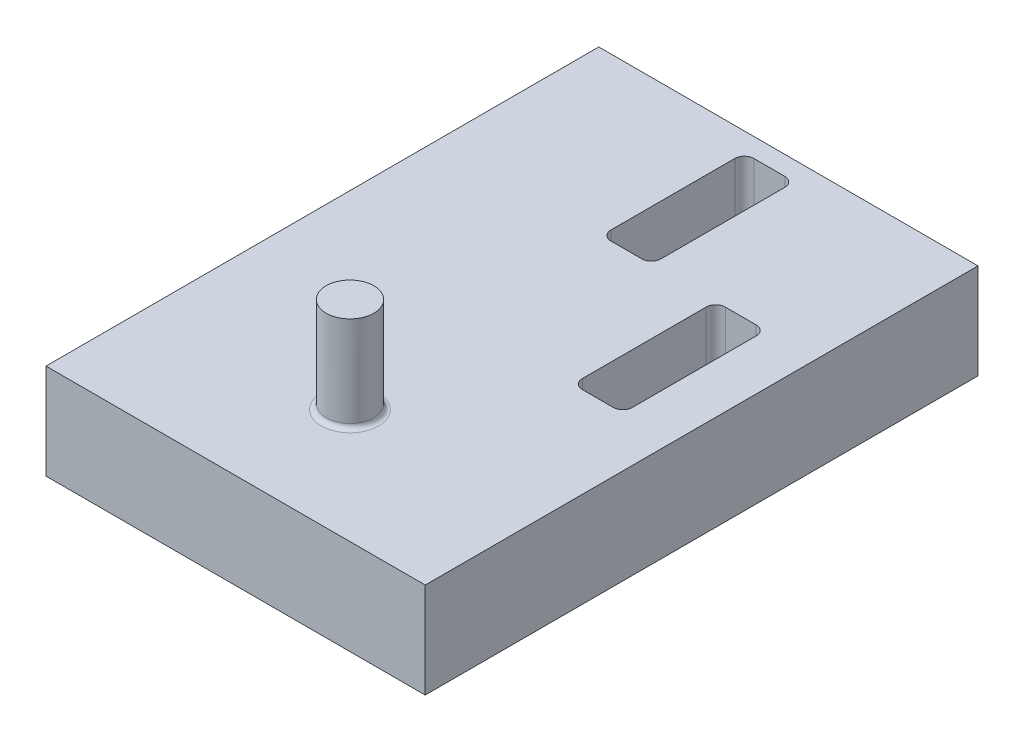
SolidWorks part; units mm, degrees
ref_plane "Front Plane" through (0, 0, 0) normal (0, 0, 1) x (1, 0, 0)
ref_plane "Top Plane" through (0, 0, 0) normal (0, 1, 0) x (1, 0, 0)
ref_plane "Right Plane" through (0, 0, 0) normal (1, 0, 0) x (0, 0, -1)
sketch "10" plane through (0, 0, 0) normal (0, 1, 0) x (1, 0, 0)
  line L0 (-15, 31.5) -> (15, 31.5) construction
  line L1 (-14.8938, 29.7182) -> (14.8938, 33.2818)
  line L2 (-14.8938, 29.7182) -> (-12, 15)
  line L3 (14.8938, 33.2818) -> (12, 48)
  line L4 (-12, 15) -> (0, 15)
  line L5 (12, 48) -> (0, 48)
  line L6 (0, 48) -> (0, 63)
  line L7 (0, 15) -> (0, 0)
  point P4 (0, 31.5)
  point P5 (0, 31.5)
  dimension "D1" = 15
  dimension "D2" = 12
  dimension "D3" = 15
  dimension "D4" = 30
  dimension "D5" = 30
  dimension "D6" = 15
  dimension "D7" = 0
  dimension "D8" = 0
  dimension "D9" = 31.5
sketch "01" plane through (0, 0, 0) normal (0, 1, 0) x (1, 0, 0)
  line L0 (-15, 31.5) -> (15, 31.5) construction
  line L1 (-9.3393, 19.7621) -> (9.3393, 43.2379)
  line L2 (-9.3393, 19.7621) -> (-12, 5)
  line L3 (9.3393, 43.2379) -> (12, 58)
  line L4 (-12, 5) -> (0, 5)
  line L5 (12, 58) -> (0, 58)
  line L6 (0, 58) -> (0, 73)
  line L7 (0, 5) -> (0, -10)
  point P4 (0, 31.5)
  point P5 (0, 31.5)
  dimension "D1" = 30
  dimension "D2" = 15
  dimension "D3" = 12
  dimension "D4" = 15
  dimension "D5" = 30
  dimension "D6" = 0
  dimension "D7" = 41.5
  dimension "D8" = 0
  dimension "D9" = 15
sketch "Sketch2" plane through (0, 0, 0) normal (0, 1, 0) x (1, 0, 0)
  line L1 (-19.8938, 77.5) -> (0, 77.5)
  line L2 (-19.8938, 77.5) -> (-19.8938, -14.5)
  line L3 (-19.8938, -14.5) -> (0, -14.5)
  line L9 (-15, 31.5) -> (15, 31.5) construction
  line L24 (0, 77.5) -> (0, 75.5)
  line L25 (-2.625, 73) -> (-2.625, 63)
  line L26 (0, 75.5) -> (-2.625, 75.5)
  line L27 (-2.625, 75.5) -> (-2.625, 73)
  line L28 (0, 60.5) -> (-2.625, 60.5)
  line L29 (-2.625, 60.5) -> (-2.625, 63)
  line L32 (0, 60.375) -> (0, 2.5)
  line L34 (0, 60.5) -> (0, 60.375)
  line L35 (-2.625, 0) -> (-2.625, -10)
  line L36 (0, 2.5) -> (-2.625, 2.5)
  line L37 (-2.625, 2.5) -> (-2.625, 0)
  line L38 (0, -12.5) -> (-2.625, -12.5)
  line L39 (-2.625, -12.5) -> (-2.625, -10)
  line L41 (0, -12.5) -> (0, -14.5)
  circle A7 centre (-14.8938, 29.7182) radius 5 construction
  circle A19 centre (0, 73) radius 2.625 construction
  circle A21 centre (0, 63) radius 2.625 construction
  circle A22 centre (0, 73) radius 2.5 construction
  circle A23 centre (0, 63) radius 2.5 construction
  circle A24 centre (0, -10) radius 2.625 construction
  circle A25 centre (0, 0) radius 2.625 construction
  circle A26 centre (0, 0) radius 2.5 construction
  circle A27 centre (0, -10) radius 2.5 construction
  dimension "D2" = 5.25
  dimension "D3" = 5.25
  dimension "D4" = 5
  dimension "D5" = 5
  dimension "D8" = 10
  dimension "D7" = 10
  dimension "D9" = 5.25
  dimension "D12" = 5.25
  dimension "D14" = 5
  dimension "D15" = 5
  dimension "D6" = 2
  dimension "D10" = 19.8938
  dimension "D11" = 5
  dimension "D13" = 19.8938
  dimension "D16" = 10
  dimension "D17" = 2
  dimension "D18" = 57.875
extrude "Boss-Extrude1" add sketch "Sketch2" along normal blind 10 contours L2 L3 L41 L38 L39 L35 L37 L36 L32 L34 L28 L29 L25 L27 L26 L24 L1
fillet "Fillet2" radius 1 4 edges at (-2.625, 5, 12.5) (-2.625, 5, -2.5) (-2.625, 5, -60.5) (-2.625, 5, -75.5)
mirror "Mirror1" of "Fillet2", "Boss-Extrude1"
sketch "Sketch4" plane through (0, 0, 0) normal (0, 1, 0) x (1, 0, 0)
  line L0 (-14.625, 15) -> (-14.625, 5)
  line L1 (-9.375, 15) -> (-9.375, 5)
  line L2 (-12, 2.5) -> (-9.375, 2.5)
  line L3 (-9.375, 2.5) -> (-9.375, 5)
  line L4 (-12, 2.5) -> (-14.625, 2.5)
  line L5 (-14.625, 2.5) -> (-14.625, 5)
  line L6 (-12, 17.5) -> (-9.375, 17.5)
  line L7 (-9.375, 17.5) -> (-9.375, 15)
  line L9 (-12, 17.5) -> (-14.625, 17.5)
  line L10 (-14.625, 17.5) -> (-14.625, 15)
  line L12 (9.375, 58) -> (9.375, 48)
  line L13 (14.625, 58) -> (14.625, 48)
  line L16 (12, 60.5) -> (9.375, 60.5)
  line L17 (9.375, 60.5) -> (9.375, 58)
  line L19 (12, 60.5) -> (14.625, 60.5)
  line L20 (14.625, 60.5) -> (14.625, 58)
  line L21 (12, 45.5) -> (14.625, 45.5)
  line L22 (14.625, 45.5) -> (14.625, 48)
  line L23 (12, 45.5) -> (9.375, 45.5)
  line L24 (9.375, 45.5) -> (9.375, 48)
  circle A0 centre (-12, 5) radius 2.625 construction
  circle A1 centre (-12, 15) radius 2.625 construction
  circle A14 centre (-12, 15) radius 2.5 construction
  circle A15 centre (-12, 5) radius 2.5 construction
  circle A16 centre (12, 48) radius 2.625 construction
  circle A17 centre (12, 48) radius 2.5 construction
  circle A18 centre (12, 58) radius 2.5 construction
  circle A19 centre (12, 58) radius 2.625 construction
  dimension "D1" = 5.25
  dimension "D2" = 5
extrude "Cut-Extrude1" cut sketch "Sketch4" along normal through all
fillet "Fillet3" radius 1 8 edges at (9.375, 5, -45.5) (14.625, 5, -45.5) (9.375, 5, -60.5) (14.625, 5, -60.5) (-14.625, 5, -2.5) (-9.375, 5, -2.5) (-9.375, 5, -17.5) (-14.625, 5, -17.5)
sketch "Sketch5" plane through (0, 10, 0) normal (0, 1, 0) x (1, 0, 0)
  line L0 (-14.8938, 29.7182) -> (14.8938, 33.2818) construction
  circle A0 centre (0, 31.5) radius 2.5
  dimension "D1" = 5
extrude "Boss-Extrude2" add sketch "Sketch5" along normal blind 10
fillet "Fillet1" radius 0.5 1 edges at (0, 10, -34)
sketch "Sketch6" plane through (0, 10, 0) normal (0, 1, 0) x (1, 0, 0)
  line L9 (19.8938, 77.5) -> (19.8938, -14.5) construction
  line L22 (19.8938, 19.5) -> (-51.3, 19.5) construction
  line L23 (-19.8938, -14.5) -> (19.8938, -14.5)
  line L24 (-19.8938, -14.5) -> (-19.8938, 19.5)
  line L25 (-19.8938, 19.5) -> (19.8938, 19.5)
  line L26 (19.8938, -14.5) -> (19.8938, 19.5)
extrude "Cut-Extrude2" cut sketch "Sketch6" against normal blind 10
